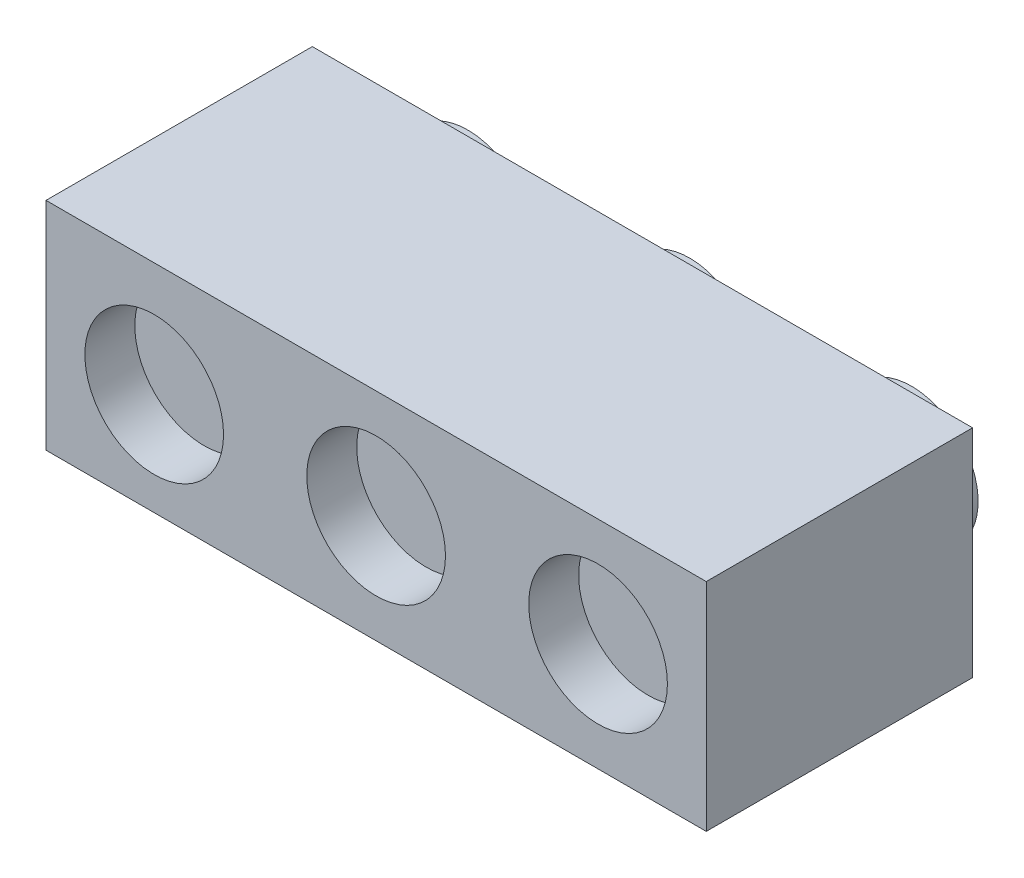
SolidWorks part; units mm, degrees
ref_plane "Спереди" through (0, 0, 0) normal (0, 0, 1) x (1, 0, 0)
ref_plane "Сверху" through (0, 0, 0) normal (0, 1, 0) x (1, 0, 0)
ref_plane "Справа" through (0, 0, 0) normal (1, 0, 0) x (0, 0, -1)
sketch "Эскиз1" plane through (0, 0, 0) normal (0, 0, 1) x (1, 0, 0)
  line L1 (-11.9, -3.9) -> (11.9, -3.9)
  line L2 (-11.9, -3.9) -> (-11.9, 3.9)
  line L3 (-11.9, 3.9) -> (11.9, 3.9)
  line L4 (11.9, -3.9) -> (11.9, 3.9)
  line L5 (-11.9, -3.9) -> (11.9, 3.9) construction
  line L6 (-11.9, 3.9) -> (11.9, -3.9) construction
  point P0 (0, 0)
  dimension "D1" = 23.8
  dimension "D2" = 7.8
extrude "Бобышка-Вытянуть1" add sketch "Эскиз1" along normal blind 9.6
sketch "Эскиз2" plane through (0, 0, 0) normal (0, 0, -1) x (-1, 0, 0)
  circle A0 centre (0, 0) radius 2.4
  circle A1 centre (8, 0) radius 2.4
  circle A2 centre (-8, 0) radius 2.4
  dimension "D1" = 8
  dimension "D2" = 8
extrude "Бобышка-Вытянуть2" add sketch "Эскиз2" along normal blind 1.7
sketch "Эскиз3" plane through (0, 0, 9.6) normal (0, 0, 1) x (1, 0, 0)
  circle A0 centre (0, 0) radius 2.5
  circle A1 centre (-8, -0.2111) radius 2.5
  circle A2 centre (8, 0) radius 2.5
  dimension "D1" = 8
  dimension "D2" = 8
extrude "Вырез-Вытянуть1" cut sketch "Эскиз3" against normal blind 1.8
